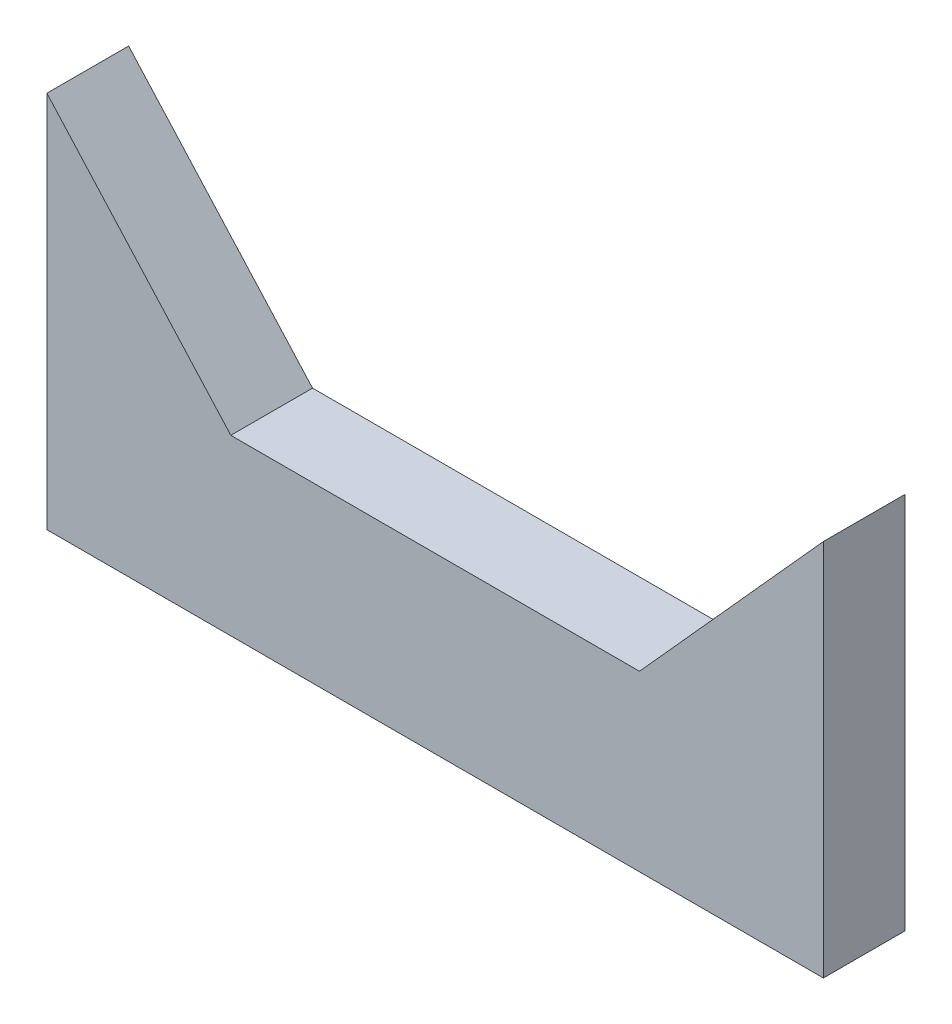
SolidWorks part; units mm, degrees
ref_plane "Front Plane" through (0, 0, 0) normal (0, 0, 1) x (1, 0, 0)
ref_plane "Top Plane" through (0, 0, 0) normal (0, 1, 0) x (1, 0, 0)
ref_plane "Right Plane" through (0, 0, 0) normal (1, 0, 0) x (0, 0, -1)
sketch "Sketch1" plane through (0, 0, 0) normal (0, 0, 1) x (1, 0, 0)
  line L0 (19, 8.3043) -> (19, -10.1957)
  line L1 (19, -10.1957) -> (-19, -10.1957)
  line L2 (19, 8.3043) -> (10, -1.6957)
  line L3 (10, -1.6957) -> (-10, -1.6957)
  line L4 (0, -11.047) -> (0, 6.688) construction
  line L5 (-19, 8.3043) -> (-10, -1.6957)
  line L6 (-19, 8.3043) -> (-19, -10.1957)
  point P9 (0, -1.6957)
  point P11 (0, -10.1957)
  dimension "D1" = 38
  dimension "D2" = 18.5
  dimension "D3" = 10
  dimension "D4" = 20
extrude "Boss-Extrude1" add sketch "Sketch1" along normal blind 4
